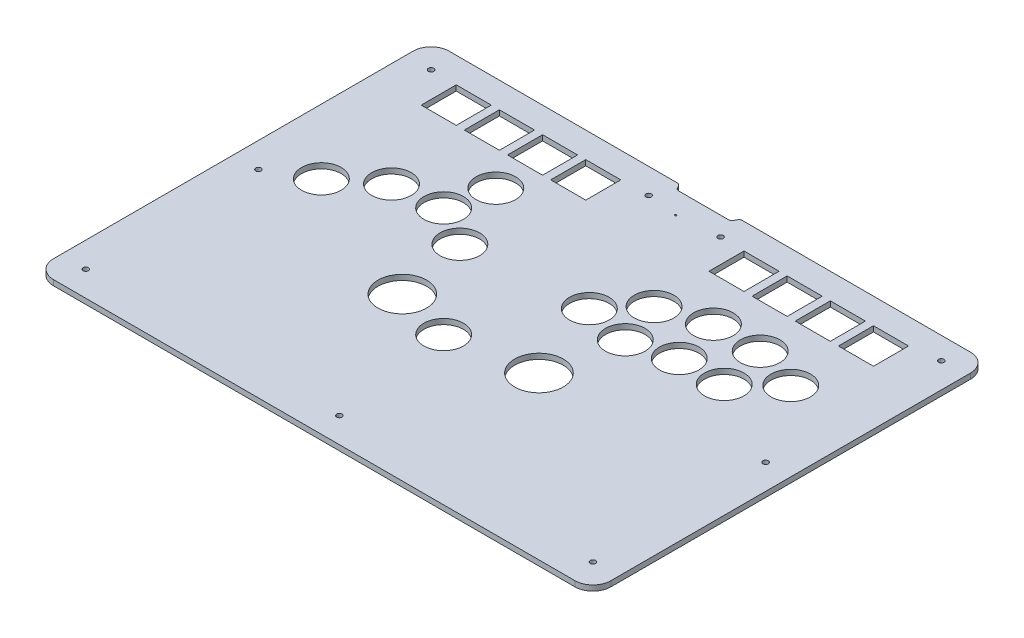
SolidWorks part; units mm, degrees
ref_plane "前视基准面" through (0, 0, 0) normal (0, 0, 1) x (1, 0, 0)
ref_plane "上视基准面" through (0, 0, 0) normal (0, 1, 0) x (1, 0, 0)
ref_plane "右视基准面" through (0, 0, 0) normal (1, 0, 0) x (0, 0, -1)
sketch "草图1" plane through (0, 0, 0) normal (0, 1, 0) x (1, 0, 0)
  line L1 (10, 0) -> (136.8844, 0)
  line L2 (0, -10) -> (0, -210)
  line L3 (10, -220) -> (300, -220)
  line L4 (310, -10) -> (310, -210)
  line L5 (28.25, -14.25) -> (47.75, -14.25)
  line L6 (28.25, -14.25) -> (28.25, -33.75)
  line L7 (28.25, -33.75) -> (47.75, -33.75)
  line L8 (173, -85) -> (173, 0) construction
  line L9 (173, -85) -> (310, -85) construction
  line L10 (190, -66) -> (190, 0) construction
  line L11 (215, -58) -> (215, 0) construction
  line L12 (241, -58) -> (241, 0) construction
  line L13 (247, -84) -> (247, 0) construction
  line L14 (222, -84) -> (222, 0) construction
  line L15 (0, -220) -> (310, 0) construction
  line L16 (241, -58) -> (310, -58) construction
  line L17 (247, -84) -> (310, -84) construction
  line L18 (215, -58) -> (310, -58) construction
  line L19 (222, -84) -> (310, -84) construction
  line L20 (190, -66) -> (310, -66) construction
  line L21 (310, -220) -> (0, 0) construction
  line L22 (141.1791, -3.5) -> (168.8209, -3.5)
  line L23 (139.4291, -2.4682) -> (138.6344, -1.0318)
  line L24 (170.5709, -2.4682) -> (171.3656, -1.0318)
  line L25 (173.1156, 0) -> (300, 0)
  line L26 (155, -110) -> (155, -220) construction
  line L27 (47.75, -14.25) -> (47.75, -33.75)
  line L28 (28.25, -14.25) -> (47.75, -33.75) construction
  line L29 (28.25, -33.75) -> (47.75, -14.25) construction
  line L30 (52.25, -14.25) -> (71.75, -14.25)
  line L31 (52.25, -14.25) -> (52.25, -33.75)
  line L32 (52.25, -33.75) -> (71.75, -33.75)
  line L33 (71.75, -14.25) -> (71.75, -33.75)
  line L34 (52.25, -14.25) -> (71.75, -33.75) construction
  line L35 (52.25, -33.75) -> (71.75, -14.25) construction
  line L36 (76.25, -14.25) -> (95.75, -14.25)
  line L37 (76.25, -14.25) -> (76.25, -33.75)
  line L38 (76.25, -33.75) -> (95.75, -33.75)
  line L39 (95.75, -14.25) -> (95.75, -33.75)
  line L40 (76.25, -14.25) -> (95.75, -33.75) construction
  line L41 (76.25, -33.75) -> (95.75, -14.25) construction
  line L42 (100.25, -14.25) -> (119.75, -14.25)
  line L43 (100.25, -14.25) -> (100.25, -33.75)
  line L44 (100.25, -33.75) -> (119.75, -33.75)
  line L45 (119.75, -14.25) -> (119.75, -33.75)
  line L46 (100.25, -14.25) -> (119.75, -33.75) construction
  line L47 (100.25, -33.75) -> (119.75, -14.25) construction
  line L48 (188.25, -14.25) -> (207.75, -14.25)
  line L49 (188.25, -14.25) -> (188.25, -33.75)
  line L50 (188.25, -33.75) -> (207.75, -33.75)
  line L51 (207.75, -14.25) -> (207.75, -33.75)
  line L52 (188.25, -14.25) -> (207.75, -33.75) construction
  line L53 (188.25, -33.75) -> (207.75, -14.25) construction
  line L54 (212.25, -14.25) -> (231.75, -14.25)
  line L55 (212.25, -14.25) -> (212.25, -33.75)
  line L56 (212.25, -33.75) -> (231.75, -33.75)
  line L57 (231.75, -14.25) -> (231.75, -33.75)
  line L58 (212.25, -14.25) -> (231.75, -33.75) construction
  line L59 (212.25, -33.75) -> (231.75, -14.25) construction
  line L60 (236.25, -14.25) -> (255.75, -14.25)
  line L61 (236.25, -14.25) -> (236.25, -33.75)
  line L62 (236.25, -33.75) -> (255.75, -33.75)
  line L63 (255.75, -14.25) -> (255.75, -33.75)
  line L64 (236.25, -14.25) -> (255.75, -33.75) construction
  line L65 (236.25, -33.75) -> (255.75, -14.25) construction
  line L66 (260.25, -14.25) -> (279.75, -14.25)
  line L67 (260.25, -14.25) -> (260.25, -33.75)
  line L68 (260.25, -33.75) -> (279.75, -33.75)
  line L69 (279.75, -14.25) -> (279.75, -33.75)
  line L70 (260.25, -14.25) -> (279.75, -33.75) construction
  line L71 (260.25, -33.75) -> (279.75, -14.25) construction
  arc A0 (10, 0) -> (0, -10) centre (10, -10) ccw
  arc A1 (0, -210) -> (10, -220) centre (10, -210) ccw
  arc A2 (300, -220) -> (310, -210) centre (300, -210) ccw
  arc A3 (300, 0) -> (310, -10) centre (300, -10) cw
  circle A8 centre (173, -85) radius 11
  circle A9 centre (190, -66) radius 11
  circle A11 centre (215, -58) radius 11
  circle A12 centre (222, -84) radius 11
  circle A13 centre (247, -84) radius 11
  circle A14 centre (241, -58) radius 11
  circle A15 centre (14, -14) radius 1.5
  circle A16 centre (14, -206) radius 1.5
  circle A17 centre (296, -206) radius 1.5
  circle A18 centre (296, -12.2857) radius 1.5
  arc A19 (173.1156, 0) -> (171.3656, -1.0318) centre (173.1156, -2) ccw
  arc A20 (170.5709, -2.4682) -> (168.8209, -3.5) centre (168.8209, -1.5) cw
  arc A21 (141.1791, -3.5) -> (139.4291, -2.4682) centre (141.1791, -1.5) cw
  arc A22 (136.8844, 0) -> (138.6344, -1.0318) centre (136.8844, -2) cw
  circle A24 centre (198, -90) radius 11
  circle A25 centre (114, -130) radius 13.5
  circle A26 centre (190, -130) radius 13.5
  circle A27 centre (155, -206) radius 1.5
  circle A28 centre (175, -14) radius 1.5
  circle A29 centre (145, -138) radius 11
  circle A30 centre (106, -90) radius 11
  circle A31 centre (84, -77) radius 11
  circle A32 centre (58, -80) radius 11
  circle A33 centre (36, -97) radius 11
  circle A34 centre (89, -53) radius 11
  circle A35 centre (266, -66) radius 11
  circle A36 centre (110, -24) radius 4.5 construction
  circle A37 centre (86, -24) radius 4.5 construction
  circle A38 centre (62, -24) radius 4.5 construction
  circle A39 centre (38, -24) radius 4.5 construction
  circle A40 centre (198, -24) radius 4.5 construction
  circle A41 centre (222, -24) radius 4.5 construction
  circle A42 centre (246, -24) radius 4.5 construction
  circle A43 centre (270, -24) radius 4.5 construction
  circle A48 centre (135, -14) radius 1.5
  circle A51 centre (296, -110) radius 1.5
  circle A52 centre (14, -110) radius 1.5
  circle A53 centre (152, -16) radius 0.5
  point P8 (0, 0)
  point P12 (0, -220)
  point P15 (310, -220)
  point P18 (310, 0)
  point P70 (171.9365, 0)
  point P73 (170, -3.5)
  point P76 (140, -3.5)
  point P79 (138.0635, 0)
  dimension "D3" = 10
  dimension "D7" = 90
  dimension "D10" = 22
  dimension "D15" = 53
  dimension "D16" = 22
  dimension "D19" = 22
  dimension "D20" = 22
  dimension "D21" = 22
  dimension "D22" = 84
  dimension "D23" = 22
  dimension "D24" = 22
  dimension "D32" = 22
  dimension "D34" = 3
  dimension "D37" = 3
  dimension "D40" = 3
  dimension "D43" = 3
  dimension "D47" = 3.5
  dimension "D50" = 140
  dimension "D51" = 2
  dimension "D52" = 90
  dimension "D54" = 27
  dimension "D56" = 27
  dimension "D59" = 3
  dimension "D61" = 14
  dimension "D62" = 3
  dimension "D64" = 22
  dimension "D8" = 22
  dimension "D9" = 22
  dimension "D11" = 22
  dimension "D12" = 22
  dimension "D13" = 22
  dimension "D76" = 9
  dimension "D84" = 9
  dimension "D86" = 3
  dimension "D89" = 19.5
  dimension "D92" = 19.5
  dimension "D95" = 19.5
  dimension "D98" = 3
  dimension "D101" = 19.5
  dimension "D103" = 19.5
  dimension "D87" = 3
  dimension "D107" = 1
  dimension "D1" = 220
  dimension "D2" = 310
  dimension "D14" = 89
  dimension "D17" = 85
  dimension "D18" = 137
  dimension "D25" = 66
  dimension "D26" = 120
  dimension "D27" = 36
  dimension "D28" = 58
  dimension "D29" = 95
  dimension "D30" = 88
  dimension "D31" = 69
  dimension "D33" = 63
  dimension "D35" = 14
  dimension "D36" = 14
  dimension "D38" = 14
  dimension "D39" = 14
  dimension "D41" = 14
  dimension "D42" = 14
  dimension "D44" = 14
  dimension "D45" = 12.2857
  dimension "D46" = 4
  dimension "D48" = 30
  dimension "D49" = 4
  dimension "D53" = 112
  dimension "D55" = 114
  dimension "D57" = 90
  dimension "D58" = 120
  dimension "D60" = 14
  dimension "D63" = 135
  dimension "D65" = 82
  dimension "D66" = 145
  dimension "D67" = 97
  dimension "D68" = 80
  dimension "D69" = 58
  dimension "D70" = 84
  dimension "D71" = 77
  dimension "D72" = 90
  dimension "D73" = 106
  dimension "D74" = 44
  dimension "D75" = 66
  dimension "D78" = 24
  dimension "D79" = 110
  dimension "D80" = 24
  dimension "D82" = 24
  dimension "D83" = 24
  dimension "D85" = 40
  dimension "D88" = 19.5
  dimension "D90" = 19.5
  dimension "D91" = 19.5
  dimension "D93" = 19.5
  dimension "D94" = 19.5
  dimension "D96" = 19.5
  dimension "D97" = 19.5
  dimension "D99" = 14
  dimension "D100" = 135
  dimension "D102" = 19.5
  dimension "D104" = 19.5
  dimension "D105" = 19.5
  dimension "D106" = 19.5
  dimension "D108" = 16
  dimension "D109" = 152
  dimension "D77" = 4
  dimension "D81" = 4
extrude "凸台-拉伸1" add sketch "草图1" along normal blind 3
